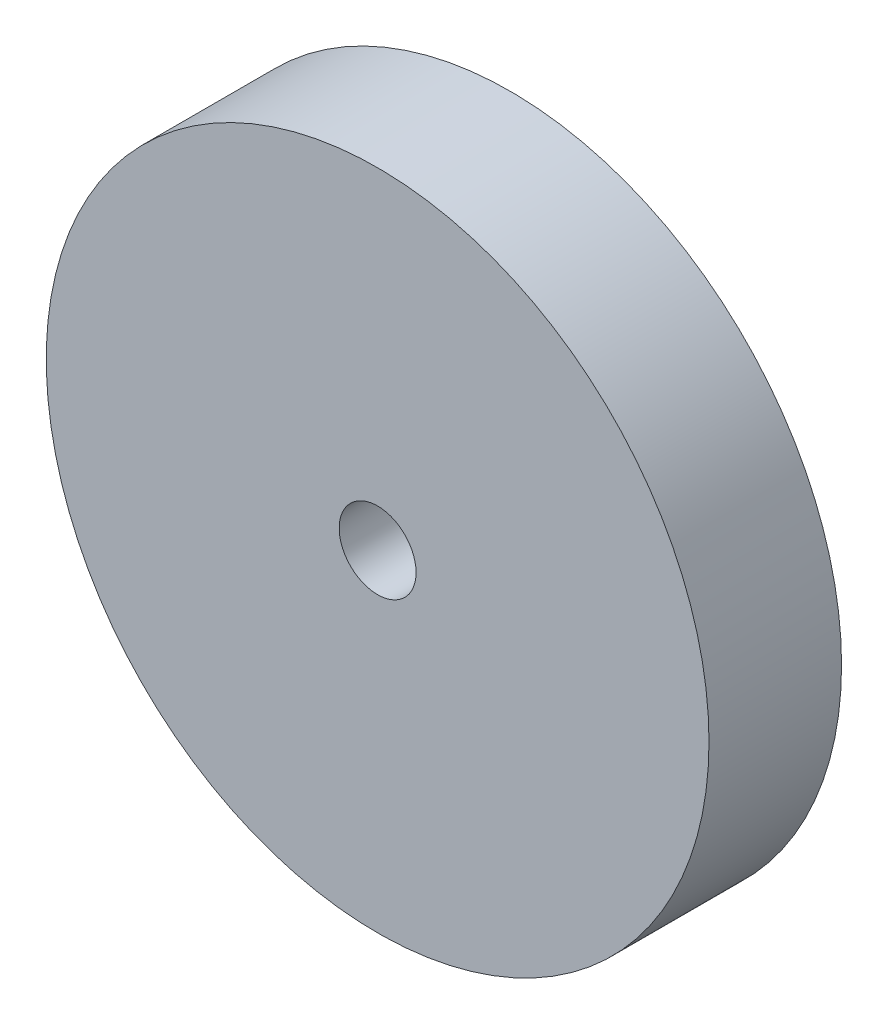
SolidWorks part; units mm, degrees
ref_plane "Front Plane" through (0, 0, 0) normal (0, 0, 1) x (1, 0, 0)
ref_plane "Top Plane" through (0, 0, 0) normal (0, 1, 0) x (1, 0, 0)
ref_plane "Right Plane" through (0, 0, 0) normal (1, 0, 0) x (0, 0, -1)
sketch "Sketch1" plane through (0, 0, 0) normal (0, 0, 1) x (1, 0, 0)
  circle A0 centre (0, 0) radius 12.7
  dimension "D1" = 25.4
extrude "Boss-Extrude1" add sketch "Sketch1" along normal blind 5.08
sketch "Sketch2" plane through (0, 0, 5.08) normal (0, 0, 1) x (1, 0, 0)
  circle A0 centre (0, 0) radius 1.4732
  dimension "D1" = 2.9464
extrude "Cut-Extrude1" cut sketch "Sketch2" against normal through all
